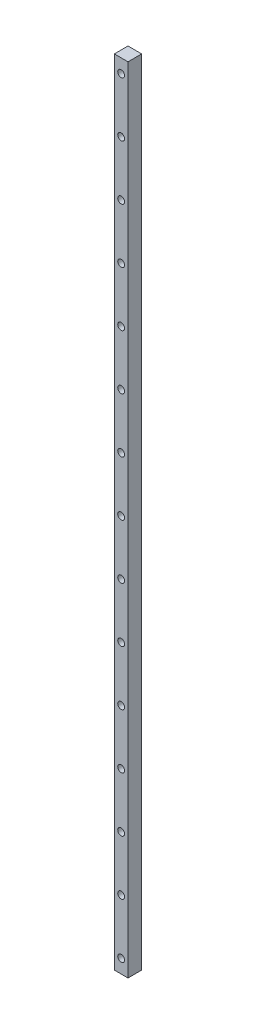
SolidWorks part; units mm, degrees
ref_plane "前视基准面" through (0, 0, 0) normal (0, 0, 1) x (1, 0, 0)
ref_plane "上视基准面" through (0, 0, 0) normal (0, 1, 0) x (1, 0, 0)
ref_plane "右视基准面" through (0, 0, 0) normal (1, 0, 0) x (0, 0, -1)
sketch "草图1" plane through (0, 0, 0) normal (0, 1, 0) x (1, 0, 0)
  line L1 (-7.5, 0) -> (7.5, 0)
  line L2 (-7.5, 0) -> (-7.5, -15)
  line L3 (-7.5, -15) -> (7.5, -15)
  line L4 (7.5, 0) -> (7.5, -15)
  dimension "D1" = 15
  dimension "D2" = 15
extrude "凸台-拉伸1" add sketch "草图1" along normal mid plane 870
hole_wizard "孔1" positions "草图4" profile "草图3" legacy
sketch "草图4" plane through (0, 0, 15) normal (0, 0, 1) x (1, 0, 0)
  line L0 (0, 435) -> (0, 420) construction
  line L1 (-7.5, 435) -> (7.5, 435) construction
  point P1 (0, 420)
  dimension "D1" = 15
sketch "草图3" plane through (0, 420, 15) normal (1, 0, 0) x (0, -1, 0)
  line L0 (0, 0) -> (0, 60)
  line L1 (0, 60) -> (2.25, 60)
  line L2 (2.25, 60) -> (2.25, 5.3)
  line L3 (2.25, 5.3) -> (3.75, 5.3)
  line L4 (3.75, 5.3) -> (3.75, 0)
  line L5 (3.75, 0) -> (0, 0)
  line L6 (0, 110) -> (0, -10) construction
  dimension "直径" = 4.5
  dimension "深度" = 60
  dimension "柱坑直径" = 7.5
  dimension "柱坑深度" = 5.3
pattern_linear "阵列(线性)1" count 15 spacing 60 along (0, -1, 0) of "孔1"
